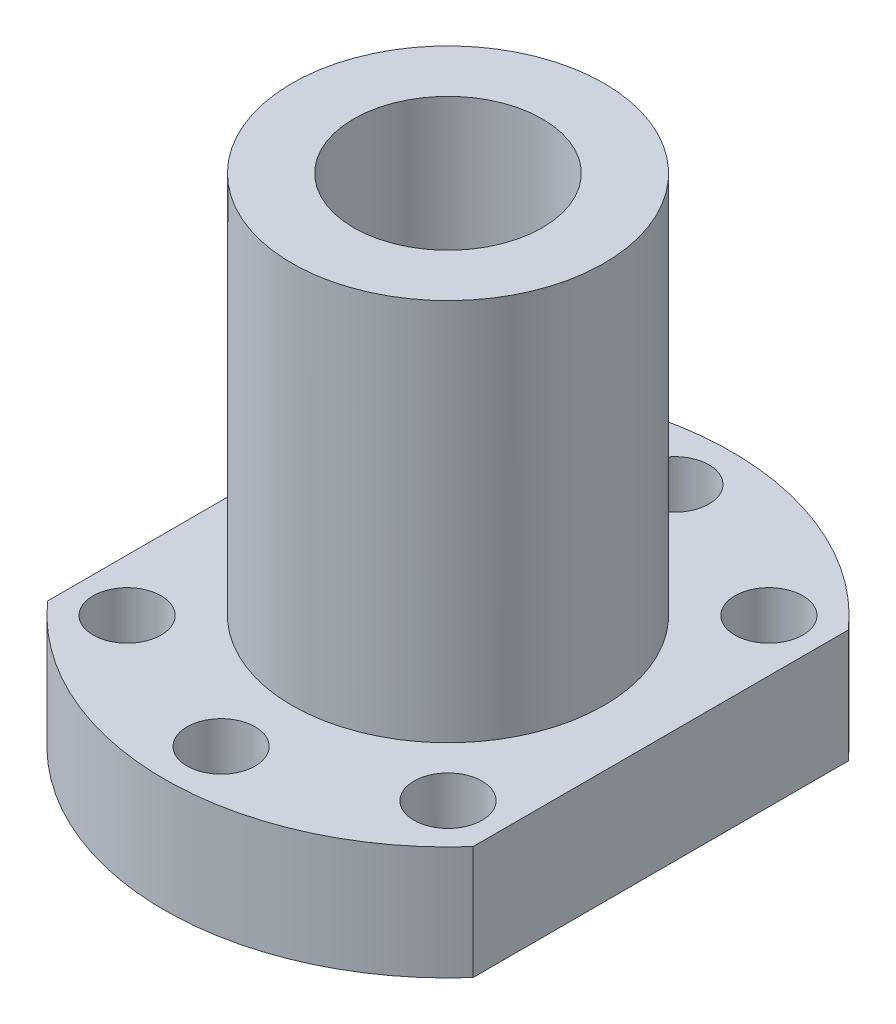
SolidWorks part; units mm, degrees
ref_plane "前视基准面" through (0, 0, 0) normal (0, 0, 1) x (1, 0, 0)
ref_plane "上视基准面" through (0, 0, 0) normal (0, 1, 0) x (1, 0, 0)
ref_plane "右视基准面" through (0, 0, 0) normal (1, 0, 0) x (0, 0, -1)
other "Configuration Table"
sketch "草图1" plane through (0, 0, 0) normal (0, 1, 0) x (1, 0, 0)
  circle A0 centre (0, 0) radius 20
  dimension "D1" = 40
extrude "凸台-拉伸1" add sketch "草图1" along normal blind 8
sketch "草图3" plane through (0, 0, 0) normal (0, -1, 0) x (1, 0, 0)
  circle A0 centre (0, 0) radius 11
  dimension "D1" = 22
extrude "凸台-拉伸2" add sketch "草图3" against normal blind 35
sketch "草图4" plane through (0, 0, 0) normal (0, -1, 0) x (1, 0, 0)
  line L0 (-15, 13.2288) -> (-15, -13.2288)
  line L1 (-15, -13.2288) -> (15, -13.2288) construction
  line L3 (-15, 13.2288) -> (15, 13.2288) construction
  line L5 (0, 13.2288) -> (0, -13.2288) construction
  line L6 (-15, 0) -> (15, 0) construction
  line L7 (15, 13.2288) -> (15, -13.2288)
  circle A0 centre (0, 0) radius 20 construction
  arc A1 (-15, 13.2288) -> (-15, -13.2288) centre (0, 0) ccw
  arc A2 (15, -13.2288) -> (15, 13.2288) centre (0, 0) ccw
  point P0 (0, 0)
  dimension "D1" = 30
  dimension "D2" = 26.4575
  dimension "D3" = 30
extrude "切除-拉伸1" cut sketch "草图4" against normal through all
sketch "草图6" plane through (0, 0, 0) normal (0, -1, 0) x (1, 0, 0)
  circle A0 centre (0, 0) radius 16 construction
  circle A1 centre (0, 16) radius 2.4
  circle A2 centre (11.3137, 11.3137) radius 2.4
  circle A4 centre (11.3137, -11.3137) radius 2.4
  circle A5 centre (0, -16) radius 2.4
  circle A6 centre (-11.3137, -11.3137) radius 2.4
  circle A8 centre (-11.3137, 11.3137) radius 2.4
  circle A9 centre (16, 0) radius 2.4 [skipped]
  circle A10 centre (-16, 0) radius 2.4 [skipped]
  point P21 (0, 0)
  dimension "D1" = 32
  dimension "D2" = 4.8
  dimension "D3" = 8
extrude "切除-拉伸2" cut sketch "草图6" against normal through all
sketch "草图7" plane through (0, 0, 0) normal (0, -1, 0) x (1, 0, 0)
  circle A0 centre (0, 0) radius 6.65
  dimension "D1" = 13.3
extrude "切除-拉伸3" cut sketch "草图7" against normal through all
